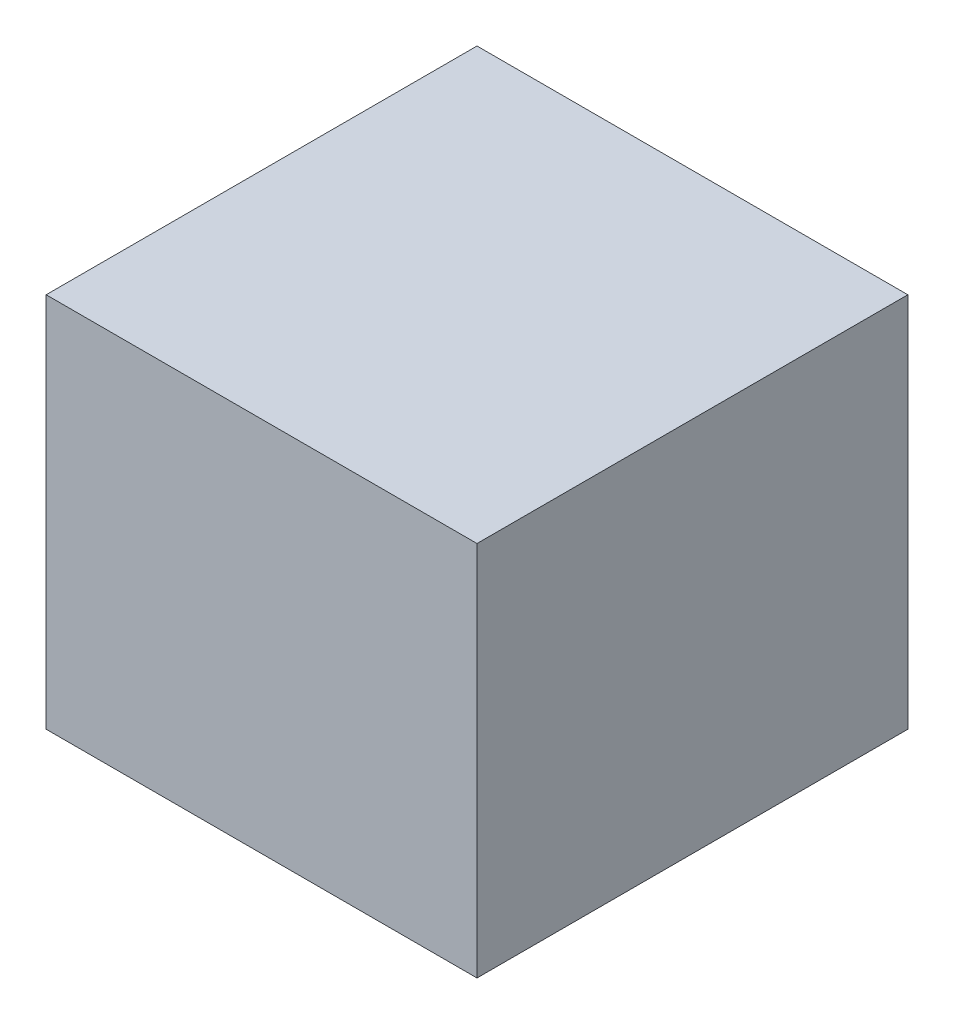
SolidWorks part; units mm, degrees
ref_plane "Front Plane" through (0, 0, 0) normal (0, 0, 1) x (1, 0, 0)
ref_plane "Top Plane" through (0, 0, 0) normal (0, 1, 0) x (1, 0, 0)
ref_plane "Right Plane" through (0, 0, 0) normal (1, 0, 0) x (0, 0, -1)
sketch "Sketch1" plane through (0, 0, 0) normal (0, 0, 1) x (1, 0, 0)
  line L1 (0, 0) -> (38.1, 0)
  line L2 (0, 0) -> (0, 33.274)
  line L3 (0, 33.274) -> (38.1, 33.274)
  line L4 (38.1, 0) -> (38.1, 33.274)
  dimension "D1" = 38.1
  dimension "D2" = 33.274
extrude "Boss-Extrude1" add sketch "Sketch1" against normal blind 38.1
